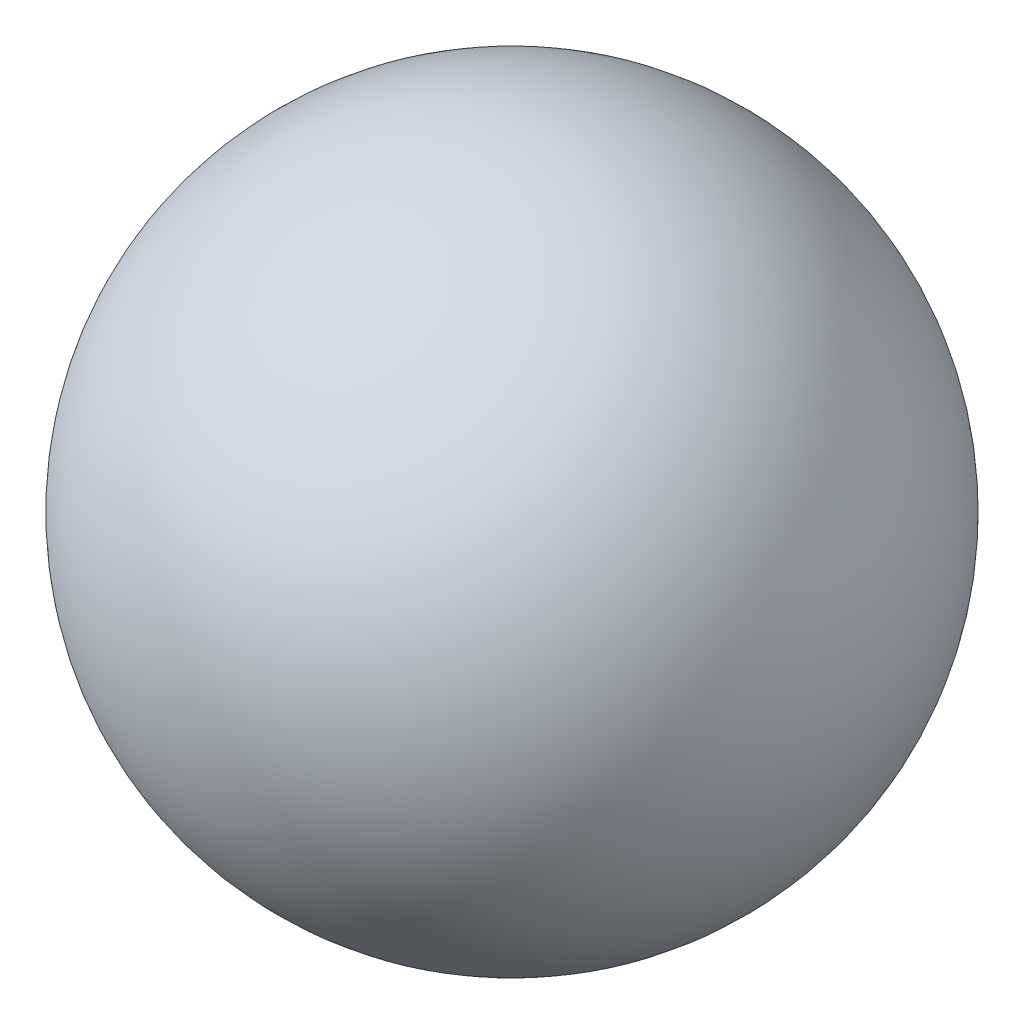
SolidWorks part; units mm, degrees
ref_plane "Front Plane" through (0, 0, 0) normal (0, 0, 1) x (1, 0, 0)
ref_plane "Top Plane" through (0, 0, 0) normal (0, 1, 0) x (1, 0, 0)
ref_plane "Right Plane" through (0, 0, 0) normal (1, 0, 0) x (0, 0, -1)
sketch "Sketch1" plane through (0, 0, 0) normal (0, 0, 1) x (1, 0, 0)
  line L0 (0, -65) -> (0, 87.5723) construction
  line L1 (0, 65) -> (0, -65)
  arc A0 (0, -65) -> (0, 65) centre (0, 0) ccw
  dimension "D1" = 130
revolve "Revolve1" add sketch "Sketch1" angle 360 about L0
